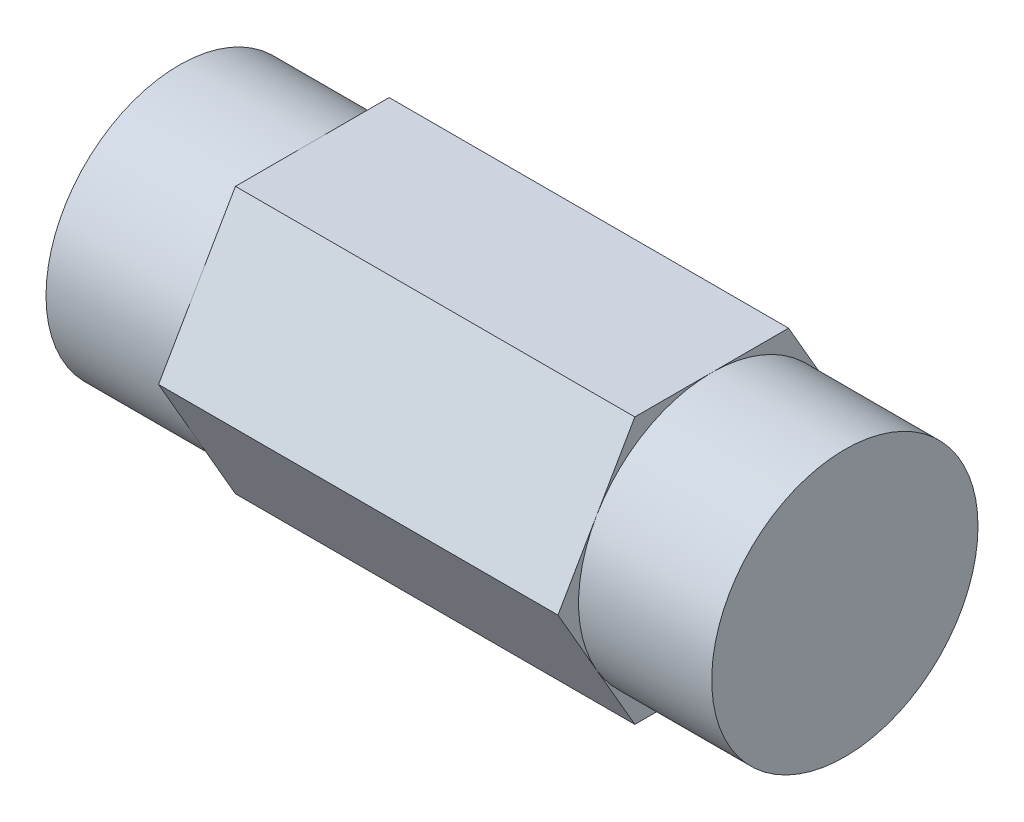
SolidWorks part; units mm, degrees
material "6061-T6 (SS)"
ref_plane "Front Plane" through (0, 0, 0) normal (0, 0, 1) x (1, 0, 0)
ref_plane "Top Plane" through (0, 0, 0) normal (0, 1, 0) x (1, 0, 0)
ref_plane "Right Plane" through (0, 0, 0) normal (1, 0, 0) x (0, 0, -1)
sketch "Sketch1" plane through (0, 0, 0) normal (1, 0, 0) x (0, 0, -1)
  line L1 (-3.6662, -6.35) -> (3.6662, -6.35)
  line L2 (3.6662, -6.35) -> (7.3323, 0)
  line L3 (7.3323, 0) -> (3.6662, 6.35)
  line L4 (3.6662, 6.35) -> (-3.6662, 6.35)
  line L5 (-3.6662, 6.35) -> (-7.3323, 0)
  line L6 (-7.3323, 0) -> (-3.6662, -6.35)
  circle A0 centre (0, 0) radius 6.35 construction
  dimension "D1" = 12.7
extrude "Boss-Extrude1" add sketch "Sketch1" along normal blind 19.05
sketch "Sketch2" plane through (19.05, 0, 0) normal (1, 0, 0) x (0, 0, -1)
  circle A0 centre (0, 0) radius 6.35
  dimension "D1" = 12.7
extrude "Boss-Extrude2" add sketch "Sketch2" along normal blind 6.35
sketch "Sketch3" plane through (0, 0, 0) normal (-1, 0, 0) x (0, 0, 1)
  circle A0 centre (0, 0) radius 6.35
  dimension "D1" = 12.7
extrude "Boss-Extrude3" add sketch "Sketch3" along normal blind 6.35
